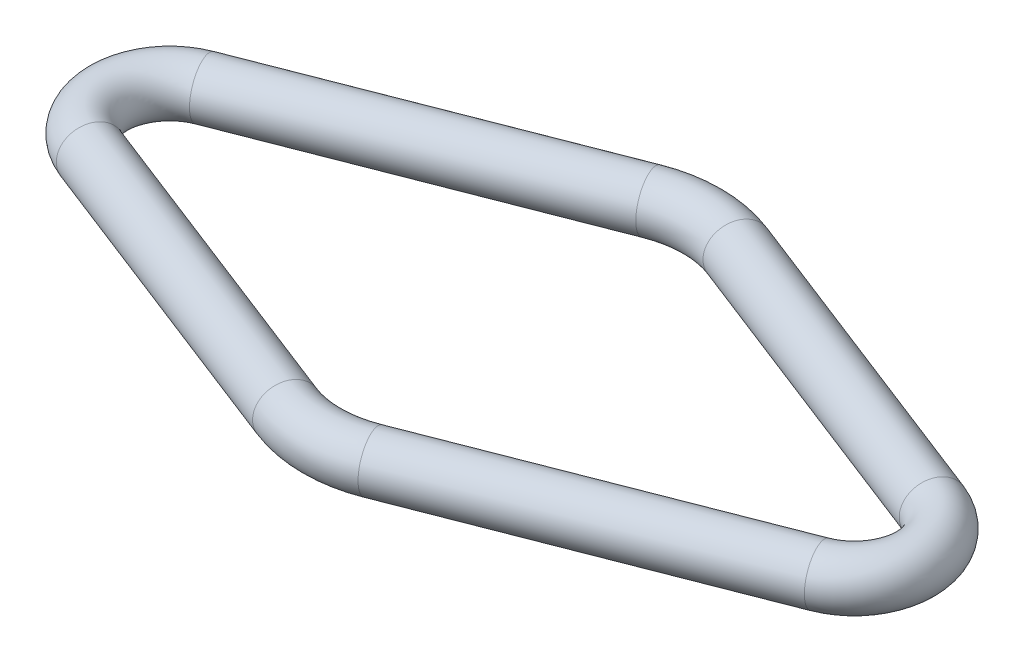
SolidWorks part; units mm, degrees
material "Silicon Rubber"
ref_plane "Front Plane" through (0, 0, 0) normal (0, 0, 1) x (1, 0, 0)
ref_plane "Top Plane" through (0, 0, 0) normal (0, 1, 0) x (1, 0, 0)
ref_plane "Right Plane" through (0, 0, 0) normal (1, 0, 0) x (0, 0, -1)
sketch "FlowPath" plane through (0, 0, 0) normal (0, 1, 0) x (1, 0, 0)
  line L0 (-10.35, 0) -> (10.35, 0) construction
  line L1 (0, -2.15) -> (0, 2.15) construction
  line L2 (0, -5.75) -> (0, 5.75) construction
  line L3 (12.2, 0) -> (-12.2, 0) construction
  line L20 (-11.0209, -1.724) -> (-1.3056, -5.5049)
  line L21 (1.3056, -5.5049) -> (11.0209, -1.724)
  line L22 (11.0209, 1.724) -> (1.3056, 5.5049)
  line L23 (-1.3056, 5.5049) -> (-11.0209, 1.724)
  arc A20 (-1.3056, -5.5049) -> (1.3056, -5.5049) centre (0, -2.15) ccw
  arc A21 (11.0209, -1.724) -> (11.0209, 1.724) centre (10.35, 0) ccw
  arc A22 (1.3056, 5.5049) -> (-1.3056, 5.5049) centre (0, 2.15) ccw
  arc A23 (-11.0209, 1.724) -> (-11.0209, -1.724) centre (-10.35, 0) ccw
  point P0 (0, 0)
  dimension "D1" = 1.85
  dimension "D2" = 3.6
  dimension "D3" = 20.7
  dimension "D4" = 11.5
  dimension "D5" = 24.4
ref_plane "O-RingProfileStartPlane" through (-1.3056, 0, 5.5049) normal (0.9319, 0, 0.3627) x (0.3627, 0, -0.9319)
sketch "Dia" plane through (-1.3056, 0, 5.5049) normal (0.9319, 0, 0.3627) x (0.3627, 0, -0.9319)
  circle A0 centre (0, 0) radius 0.8
  dimension "Dim" = 1.6
sweep "O-Ring" add profiles "Dia" path "FlowPath"
